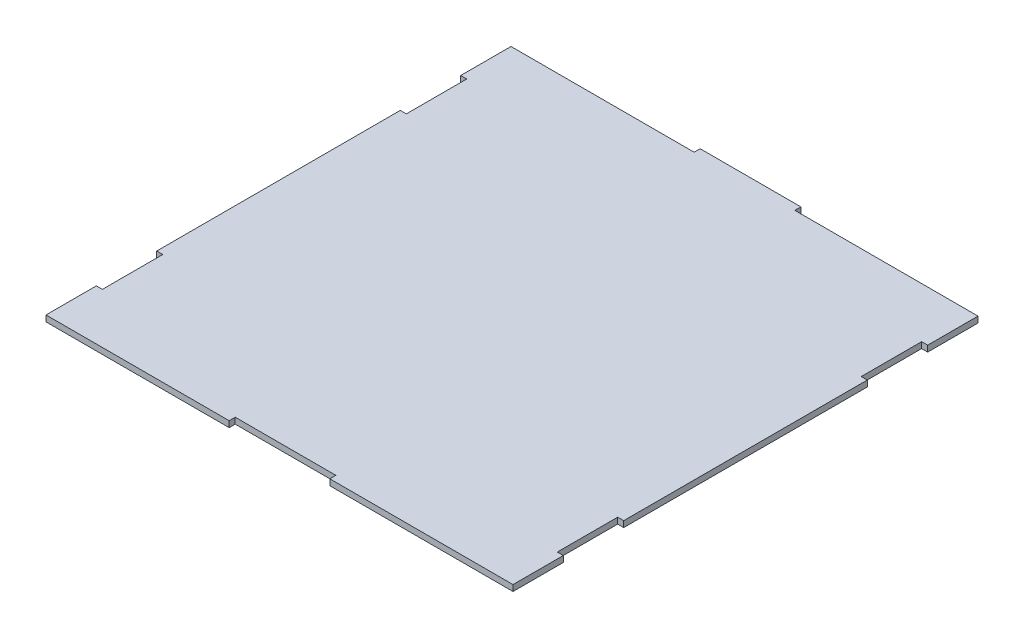
SolidWorks part; units mm, degrees
material "Teca"
ref_plane "Plano frontal" through (0, 0, 0) normal (0, 0, 1) x (1, 0, 0)
ref_plane "Plano superior" through (0, 0, 0) normal (0, 1, 0) x (1, 0, 0)
ref_plane "Plano direito" through (0, 0, 0) normal (1, 0, 0) x (0, 0, -1)
sketch "Esboço1" plane through (0, 0, 0) normal (0, 1, 0) x (1, 0, 0)
  line L0 (0, 0) -> (0, 25)
  line L1 (0, 231) -> (91, 231)
  line L2 (91, 231) -> (91, 234)
  line L3 (91, 234) -> (141, 234)
  line L4 (141, 234) -> (141, 231)
  line L5 (141, 231) -> (232, 231)
  line L6 (232, 231) -> (232, 206)
  line L7 (232, 0) -> (141, 0)
  line L8 (141, 0) -> (141, 3)
  line L9 (141, 3) -> (91, 3)
  line L10 (91, 3) -> (91, 0)
  line L11 (91, 0) -> (0, 0)
  line L12 (0, 55) -> (0, 176)
  line L13 (232, 25) -> (229, 25)
  line L15 (232, 55) -> (229, 55)
  line L16 (229, 25) -> (229, 55)
  line L17 (232, 176) -> (229, 176)
  line L19 (232, 206) -> (229, 206)
  line L20 (229, 176) -> (229, 206)
  line L21 (0, 25) -> (3, 25)
  line L23 (0, 55) -> (3, 55)
  line L24 (3, 25) -> (3, 55)
  line L25 (0, 206) -> (3, 206)
  line L27 (0, 176) -> (3, 176)
  line L28 (3, 206) -> (3, 176)
  line L29 (0, 206) -> (0, 231)
  line L30 (232, 176) -> (232, 55)
  line L31 (232, 25) -> (232, 0)
  dimension "D1" = 231
  dimension "D2" = 50
  dimension "D3" = 50
  dimension "D4" = 3
  dimension "D5" = 3
  dimension "D6" = 91
  dimension "D7" = 91
  dimension "D8" = 3
  dimension "D9" = 91
  dimension "D10" = 30
  dimension "D11" = 3
  dimension "D12" = 30
  dimension "D13" = 3
  dimension "D14" = 3
  dimension "D15" = 30
  dimension "D16" = 30
  dimension "D17" = 3
  dimension "D18" = 25
  dimension "D19" = 25
  dimension "D20" = 25
  dimension "D21" = 25
extrude "Ressalto-extrusão1" add sketch "Esboço1" along normal blind 3
